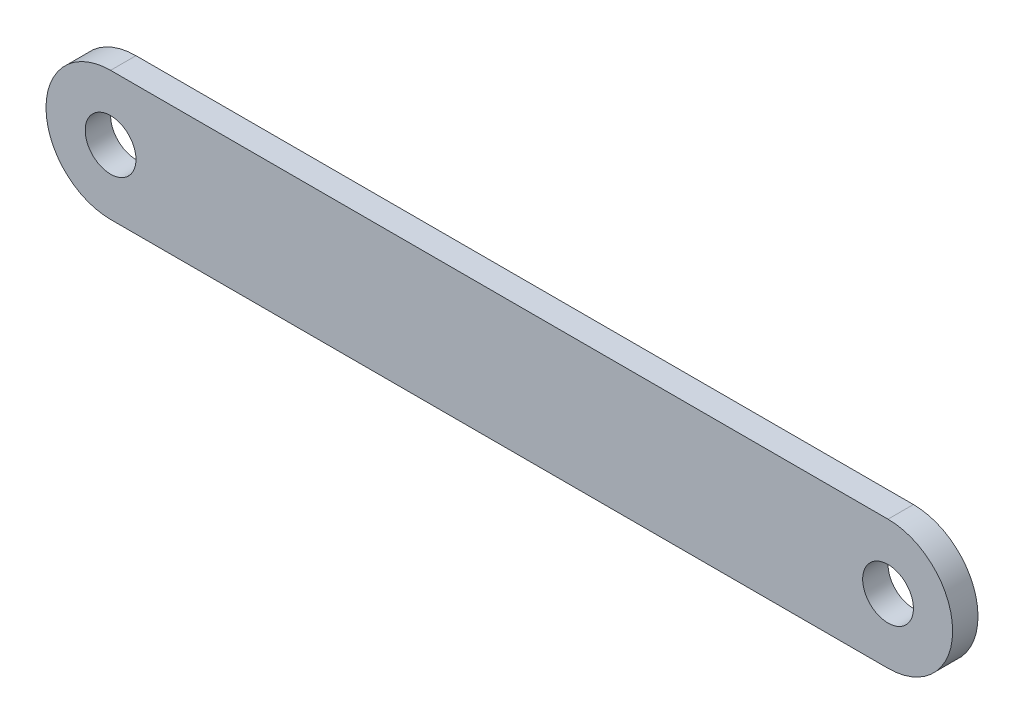
SolidWorks part; units mm, degrees
ref_plane "Plano frontal" through (0, 0, 0) normal (0, 0, 1) x (1, 0, 0)
ref_plane "Plano superior" through (0, 0, 0) normal (0, 1, 0) x (1, 0, 0)
ref_plane "Plano direito" through (0, 0, 0) normal (1, 0, 0) x (0, 0, -1)
sketch "Esboço1" plane through (0, 0, 0) normal (0, 0, 1) x (1, 0, 0)
  line L0 (-15.315, 2.5448) -> (15.315, 2.5448)
  line L1 (-15.315, 0) -> (15.315, 0) construction
  line L2 (-15.315, -2.5448) -> (15.315, -2.5448)
  arc A0 (-15.315, 2.5448) -> (-15.315, -2.5448) centre (-15.315, 0) ccw
  arc A1 (15.315, 2.5448) -> (15.315, -2.5448) centre (15.315, 0) cw
  circle A2 centre (-15.315, 0) radius 1
  circle A3 centre (15.315, 0) radius 1
  point P3 (0, 2.5448)
  dimension "D1" = 30.63
extrude "Ressalto-extrusão1" add sketch "Esboço1" along normal blind 1
